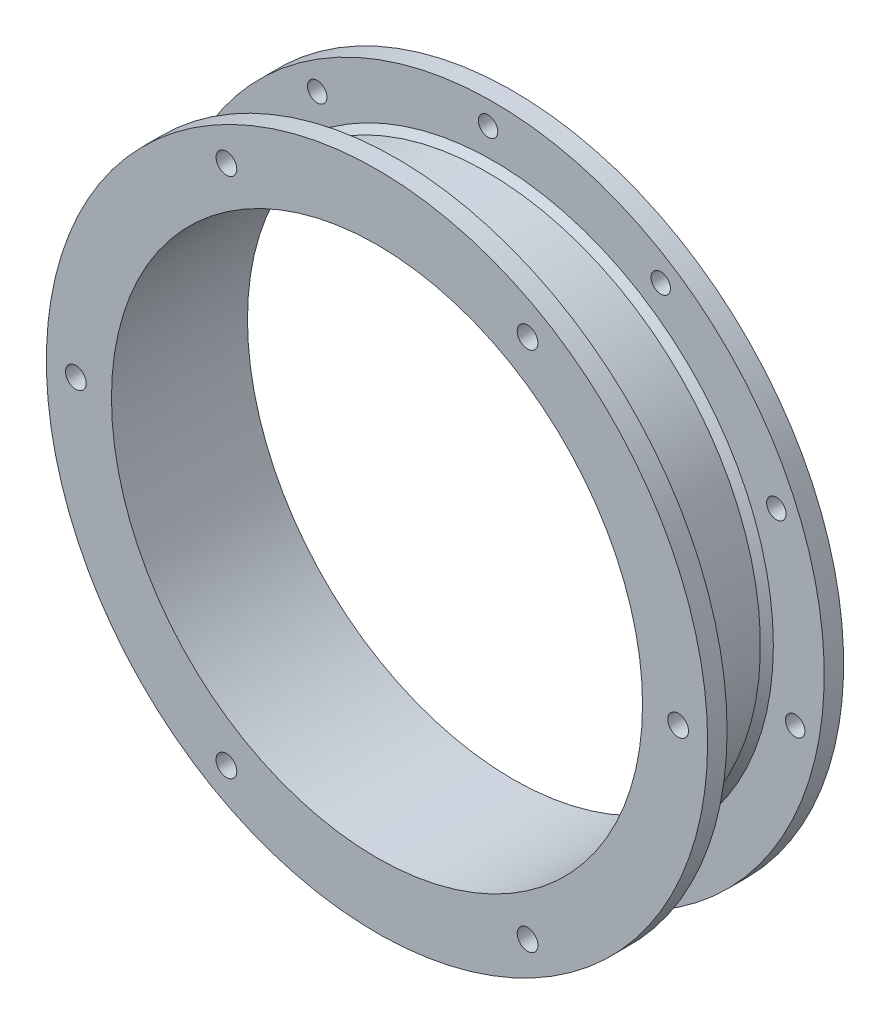
SolidWorks part; units mm, degrees
ref_plane "前视基准面" through (0, 0, 0) normal (0, 0, 1) x (1, 0, 0)
ref_plane "上视基准面" through (0, 0, 0) normal (0, 1, 0) x (1, 0, 0)
ref_plane "右视基准面" through (0, 0, 0) normal (1, 0, 0) x (0, 0, -1)
sketch "草图1" plane through (0, 0, 0) normal (0, 0, 1) x (1, 0, 0)
  circle A0 centre (-1.8002, -86) radius 42.2
  circle A2 centre (-1.8002, -86) radius 41
  arc A5 (33.4879, -106.8745) -> (-1.8002, -127) centre (-1.8002, -86) ccw construction
  dimension "D1" = 84.4
extrude "凸台-拉伸1" add sketch "草图1" along normal up to surface (21 mm away)
sketch "草图2" plane through (0, 0, 0) normal (0, 0, -1) x (-1, 0, 0)
  circle A0 centre (1.8002, -86) radius 42.2 construction
  circle A1 centre (1.8002, -86) radius 42.2
  circle A2 centre (1.8002, -86) radius 51.0553
extrude "凸台-拉伸2" add sketch "草图2" against normal blind 3
sketch "草图3" plane through (0, 0, 3) normal (0, 0, 1) x (1, 0, 0)
  circle A6 centre (44.7715, -95.0289) radius 1.5
  circle A7 centre (-2.6514, -38.5688) radius 1.5
  circle A8 centre (41.8584, -67.4427) radius 1.5
  circle A9 centre (24.0173, -46.2017) radius 1.5
  circle A10 centre (-46.0966, -69.0211) radius 1.5
  circle A11 centre (-29.0291, -47.1537) radius 1.5
extrude "切除-拉伸1" cut sketch "草图3" against normal blind 12
sketch "Sketch1" plane through (0, 0, 21) normal (0, 0, 1) x (1, 0, 0)
  line L1 (44.6998, -86) -> (21.4498, -45.7298) construction
  line L2 (21.4498, -45.7298) -> (-25.0502, -45.7298) construction
  line L3 (-25.0502, -45.7298) -> (-48.3002, -86) construction
  line L4 (-48.3002, -86) -> (-25.0502, -126.2702) construction
  line L5 (-25.0502, -126.2702) -> (21.4498, -126.2702) construction
  line L6 (21.4498, -126.2702) -> (44.6998, -86) construction
  circle A0 centre (-1.8002, -86) radius 51.0553 construction
  circle A1 centre (-1.8002, -86) radius 42.2 construction
  circle A2 centre (-1.8002, -86) radius 51.0553
  circle A3 centre (-1.8002, -86) radius 42.2
  circle A4 centre (-1.8002, -86) radius 46.5 construction
  circle A5 centre (-1.8002, -86) radius 40.2702 construction
  circle A6 centre (-25.0502, -45.7298) radius 1.6
  circle A7 centre (21.4498, -45.7298) radius 1.6
  circle A8 centre (44.6998, -86) radius 1.6
  circle A9 centre (21.4498, -126.2702) radius 1.6
  circle A10 centre (-25.0502, -126.2702) radius 1.6
  circle A11 centre (-48.3002, -86) radius 1.6
  dimension "D1" = 93
  dimension "D2" = 3.2
extrude "Extrude1" add sketch "Sketch1" against normal blind 3
chamfer "Chamfer1" distance 1 angle 45 2 edges at (40.3998, -86, 18) (-44.0002, -86, 3)
